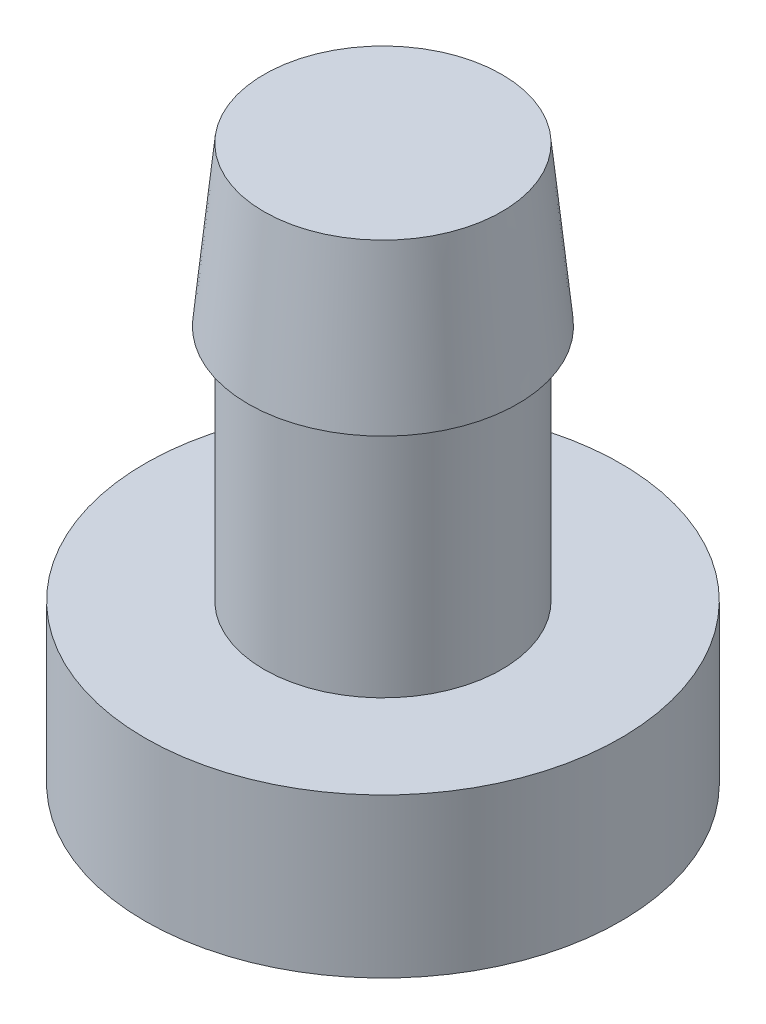
SolidWorks part; units mm, degrees
ref_plane "Front Plane" through (0, 0, 0) normal (0, 0, 1) x (1, 0, 0)
ref_plane "Top Plane" through (0, 0, 0) normal (0, 1, 0) x (1, 0, 0)
ref_plane "Right Plane" through (0, 0, 0) normal (1, 0, 0) x (0, 0, -1)
sketch "Sketch1" plane through (0, 0, 0) normal (0, 1, 0) x (1, 0, 0)
  circle A0 centre (0, 0) radius 3
  dimension "D1" = 6
extrude "Boss-Extrude1" add sketch "Sketch1" along normal blind 2
sketch "Sketch2" plane through (0, 2, 0) normal (0, 1, 0) x (1, 0, 0)
  circle A0 centre (0, 0) radius 1.5
  dimension "D1" = 3
extrude "Boss-Extrude2" add sketch "Sketch2" along normal blind 5
sketch "Sketch3" plane through (0, 0, 0) normal (0, 0, 1) x (1, 0, 0)
  line L0 (1.5, 7) -> (1.5, 5)
  line L1 (1.5, 2) -> (1.5, 7) construction
  line L2 (1.5, 5) -> (1.7, 5)
  line L3 (1.7, 5) -> (1.5, 7)
  line L4 (0, 0) -> (0, 7) construction
  line L5 (1.5, 7) -> (-1.5, 7) construction
  point P9 (0, 0)
  dimension "D1" = 0.2
  dimension "D2" = 2
revolve "Revolve1" add sketch "Sketch3" angle 360 about L4
